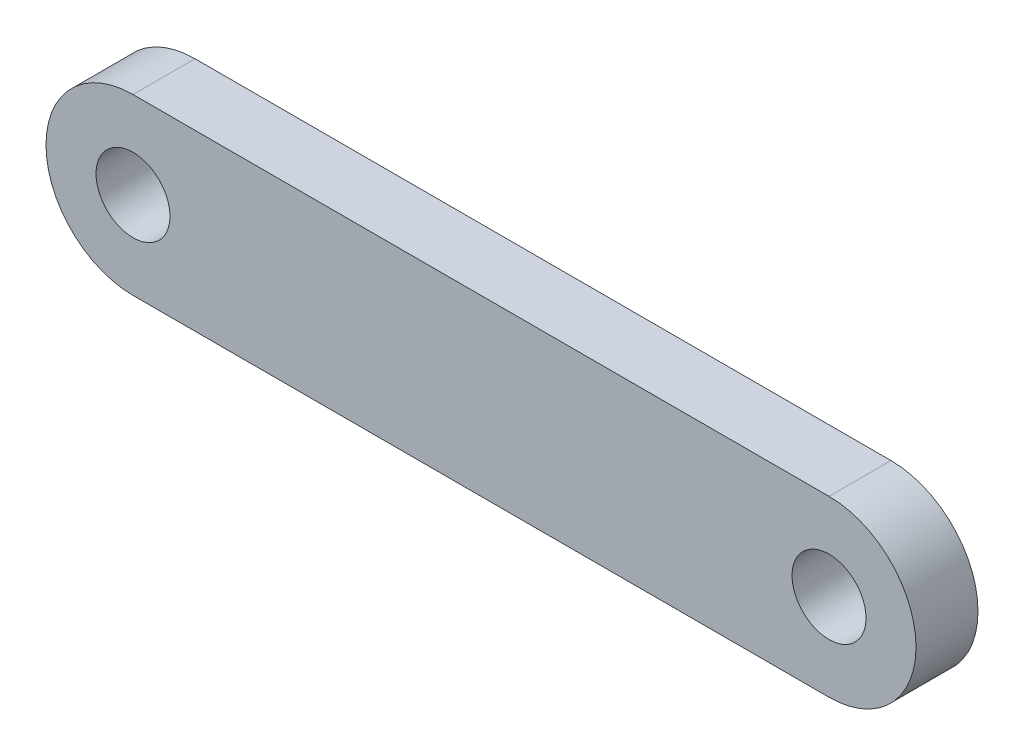
SolidWorks part; units mm, degrees
material "Pine"
ref_plane "Front" through (0, 0, 0) normal (0, 0, 1) x (1, 0, 0)
ref_plane "Top" through (0, 0, 0) normal (0, 1, 0) x (1, 0, 0)
ref_plane "Right" through (0, 0, 0) normal (1, 0, 0) x (0, 0, -1)
sketch "Sketch1" plane through (0, 0, 0) normal (0, 0, 1) x (1, 0, 0)
  line L1 (-20, 4) -> (20, 4)
  line L2 (-20, 4) -> (-20, -4)
  line L3 (-20, -4) -> (20, -4)
  line L4 (20, 4) -> (20, -4)
  line L5 (-20, 4) -> (20, -4) construction
  line L6 (-20, -4) -> (20, 4) construction
  point P0 (0, 0)
  dimension "D1" = 40
  dimension "D2" = 8
extrude "Boss-Extrude1" add sketch "Sketch1" along normal blind 2.85
sketch "Sketch2" plane through (0, 0, 2.85) normal (0, 0, 1) x (1, 0, 0)
  line L0 (16, -4) -> (21, -4)
  line L1 (21, -4) -> (21, 4)
  line L2 (21, 4) -> (16, 4)
  line L3 (20, -4) -> (20, 4) construction
  line L4 (20, 4) -> (-20, 4) construction
  line L5 (-20, -4) -> (20, -4) construction
  arc A0 (16, -4) -> (16, 4) centre (16, 0) ccw
  dimension "D1" = 1
extrude "Cut-Extrude1" cut sketch "Sketch2" against normal through all
sketch "Sketch3" plane through (0, 0, 2.85) normal (0, 0, 1) x (1, 0, 0)
  circle A0 centre (16, 0) radius 1.7
  dimension "D1" = 3.4
extrude "Cut-Extrude2" cut sketch "Sketch3" against normal through all
mirror "Mirror1" about plane through (0, 0, 0) normal (1, 0, 0) of "Cut-Extrude2", "Cut-Extrude1"
